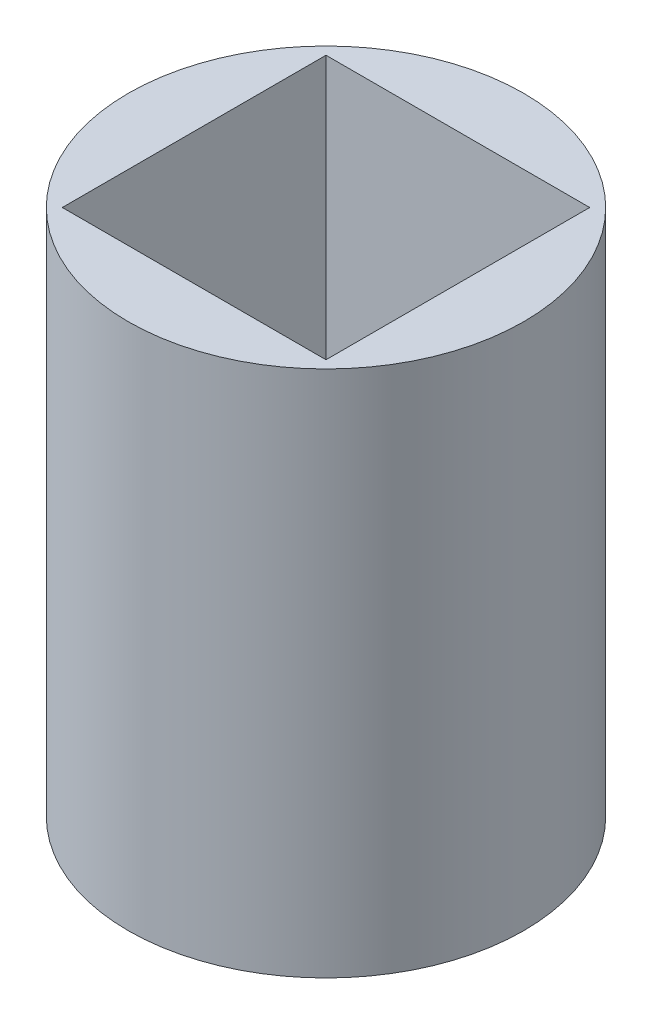
SolidWorks part; units mm, degrees
ref_plane "Front Plane" through (0, 0, 0) normal (0, 0, 1) x (1, 0, 0)
ref_plane "Top Plane" through (0, 0, 0) normal (0, 1, 0) x (1, 0, 0)
ref_plane "Right Plane" through (0, 0, 0) normal (1, 0, 0) x (0, 0, -1)
sketch "Sketch1" plane through (0, 0, 0) normal (0, 1, 0) x (1, 0, 0)
  circle A0 centre (0, 0) radius 2.25
  dimension "D1" = 4.5
extrude "Boss-Extrude1" add sketch "Sketch1" along normal blind 6
sketch "Sketch2" plane through (0, 6, 0) normal (0, 1, 0) x (1, 0, 0)
  line L1 (-1.5, -1.5) -> (1.5, -1.5)
  line L2 (-1.5, -1.5) -> (-1.5, 1.5)
  line L3 (-1.5, 1.5) -> (1.5, 1.5)
  line L4 (1.5, -1.5) -> (1.5, 1.5)
  line L5 (-1.5, -1.5) -> (1.5, 1.5) construction
  line L6 (-1.5, 1.5) -> (1.5, -1.5) construction
  point P0 (0, 0)
  dimension "D1" = 3
  dimension "D2" = 3
extrude "Cut-Extrude1" cut sketch "Sketch2" against normal through all
